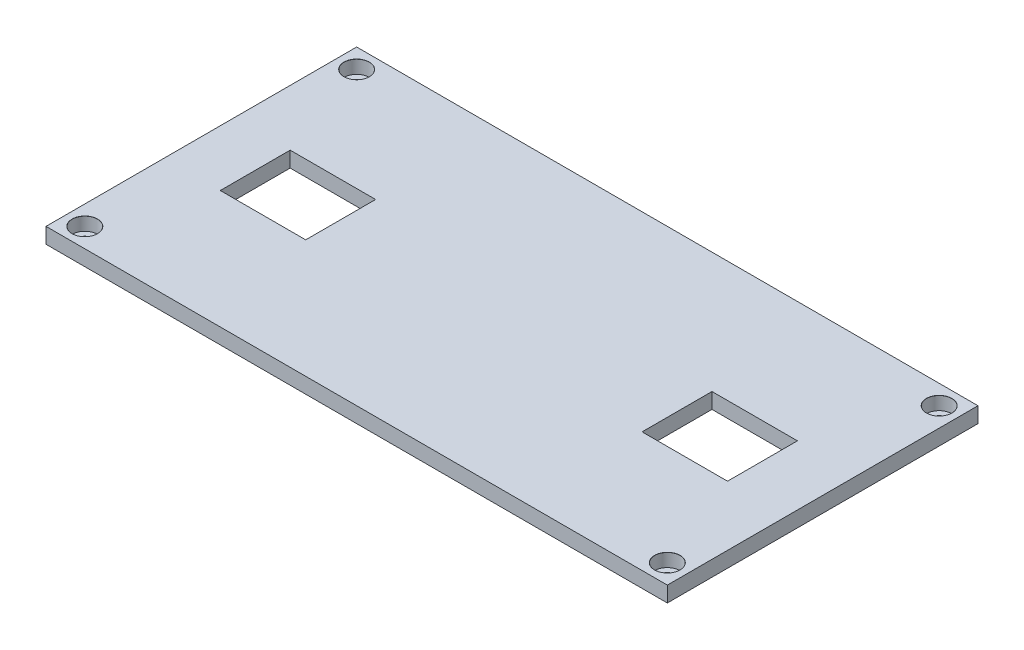
SolidWorks part; units mm, degrees
ref_plane "Front Plane" through (0, 0, 0) normal (0, 0, 1) x (1, 0, 0)
ref_plane "Top Plane" through (0, 0, 0) normal (0, 1, 0) x (1, 0, 0)
ref_plane "Right Plane" through (0, 0, 0) normal (1, 0, 0) x (0, 0, -1)
sketch "Sketch2" plane through (0, 0, 0) normal (0, 1, 0) x (1, 0, 0)
  line L1 (-80, -40) -> (80, -40)
  line L2 (-80, -40) -> (-80, 40)
  line L3 (-80, 40) -> (80, 40)
  line L4 (80, -40) -> (80, 40)
  line L5 (-80, -40) -> (80, 40) construction
  line L6 (-80, 40) -> (80, -40) construction
  point P0 (0, 0)
  dimension "D1" = 160
  dimension "D2" = 80
extrude "Boss-Extrude1" add sketch "Sketch2" along normal blind 4 contours L2 L1 L4 L3
sketch "Sketch3" plane through (0, 4, 0) normal (0, 1, 0) x (1, 0, 0)
  line L2 (-43.554, -9.5683) -> (-65.554, -9.5683)
  line L3 (-43.554, -9.5683) -> (-43.554, 8.4317)
  line L4 (-65.554, -9.5683) -> (-65.554, 8.4317)
  line L5 (-43.554, 8.4317) -> (-65.554, 8.4317)
  line L7 (64.5798, -9.0812) -> (42.5798, -9.0812)
  line L8 (64.5798, -9.0812) -> (64.5798, 8.9188)
  line L9 (42.5798, -9.0812) -> (42.5798, 8.9188)
  line L10 (64.5798, 8.9188) -> (42.5798, 8.9188)
extrude "Cut-Extrude1" cut sketch "Sketch3" against normal blind 11
hole_wizard "CBORE for M3 Hex Socket Head Cap Screw1" positions "Sketch6" profile "Sketch7" counterbore size "M3" standard "ISO" end condition through all
sketch "Sketch6" plane through (0, 4, 0) normal (0, 1, 0) x (1, 0, 0)
  line L0 (-80, -40) -> (-80, 40) construction
  line L1 (-80, 40) -> (80, 40) construction
  line L2 (-80, -40) -> (80, -40) construction
  line L3 (80, -40) -> (80, 40) construction
  point P0 (-75, 35)
  point P2 (75, 35)
  point P4 (75, -35)
  point P6 (-75, -35)
  dimension "D1" = 5
  dimension "D2" = 5
  dimension "D3" = 5
  dimension "D4" = 5
  dimension "D5" = 5
  dimension "D6" = 5
  dimension "D7" = 5
  dimension "D8" = 5
sketch "Sketch7" plane through (-75, 4, -35) normal (1, 0, 0) x (0, 0, 1)
  line L0 (0, 0) -> (0, 4)
  line L1 (0, 4) -> (1.7, 4)
  line L3 (1.7, 4) -> (1.7, 3.4)
  line L4 (3.25, 3.4) -> (1.7, 3.4)
  line L5 (3.25, 3.4) -> (3.25, 0.025)
  line L6 (3.25, 0.025) -> (3.275, 0)
  line L7 (3.275, 0) -> (0, 0)
  line L8 (-3.25, 0.025) -> (-3.275, 0) construction
  line L11 (0, -6.35) -> (0, 107.95) construction
  dimension "Thru Hole Dia." = 3.4
  dimension "Thru Hole Depth" = 4
  dimension "C'Bore Dia." = 6.5
  dimension "C'Bore Depth" = 3.4
  dimension "Near C'Sink Dia." = 6.55
  dimension "Near C'Sink Angle" = 90
